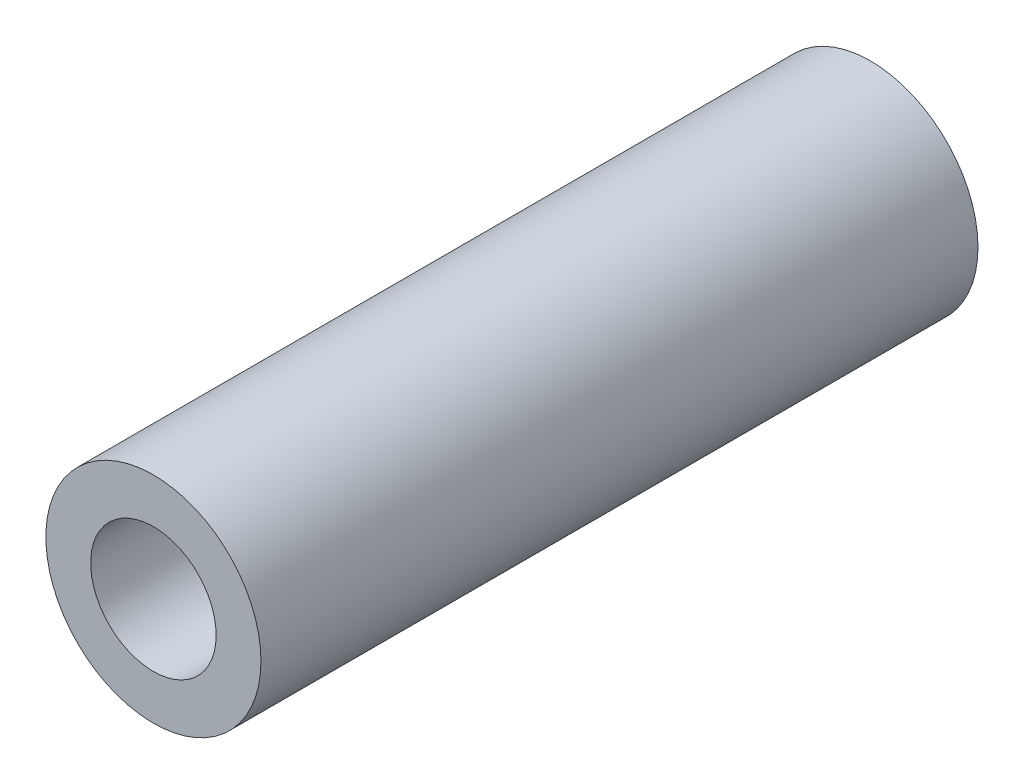
SolidWorks part; units mm, degrees
ref_plane "Front Plane" through (0, 0, 0) normal (0, 0, 1) x (1, 0, 0)
ref_plane "Top Plane" through (0, 0, 0) normal (0, 1, 0) x (1, 0, 0)
ref_plane "Right Plane" through (0, 0, 0) normal (1, 0, 0) x (0, 0, -1)
sketch "Sketch1" plane through (0, 0, 0) normal (0, 0, 1) x (1, 0, 0)
  circle A0 centre (0, 0) radius 3
  circle A1 centre (0, 0) radius 1.75
  dimension "D1" = 6
  dimension "D2" = 3.5
extrude "Boss-Extrude1" add sketch "Sketch1" along normal mid plane 20
